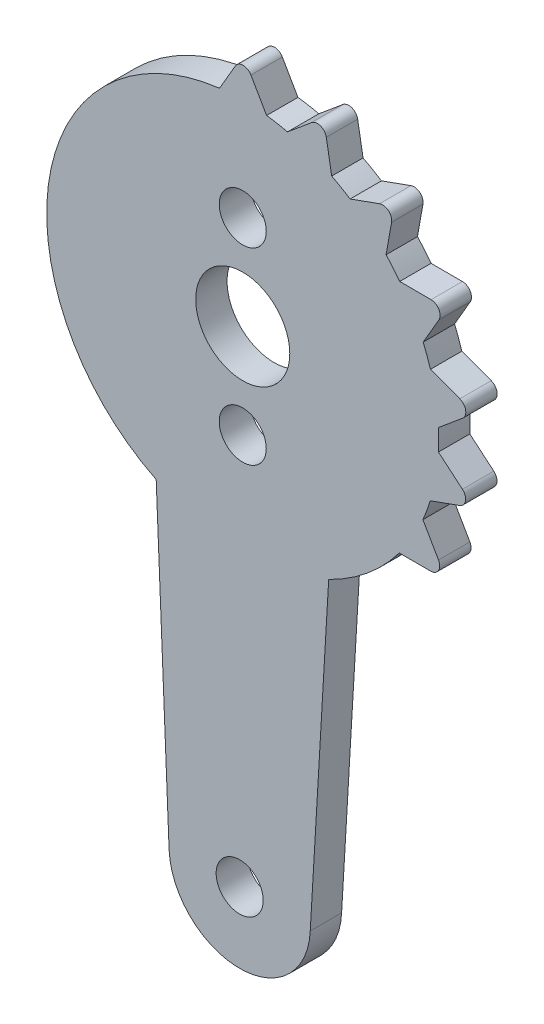
SolidWorks part; units mm, degrees
ref_plane "Front Plane" through (0, 0, 0) normal (0, 0, 1) x (1, 0, 0)
ref_plane "Top Plane" through (0, 0, 0) normal (0, 1, 0) x (1, 0, 0)
ref_plane "Right Plane" through (0, 0, 0) normal (1, 0, 0) x (0, 0, -1)
sketch "Sketch1" plane through (0, 0, 0) normal (0, 0, 1) x (1, 0, 0)
  line L0 (-5.3228, 19.8328) -> (-4.5, -0.185)
  line L1 (5.6772, 19.8147) -> (4.5, -0.1853)
  line L2 (4.5859, 44.5001) -> (3.0506, 43.2183)
  line L3 (0.7204, 45.1904) -> (1.7162, 43.4559)
  line L4 (-0.2796, 45.1904) -> (-1.2838, 43.4608)
  line L5 (5.5255, 44.158) -> (5.868, 42.1876)
  line L6 (8.9217, 42.1873) -> (7.0407, 41.5079)
  line L7 (9.6878, 41.5445) -> (9.3356, 39.5758)
  line L8 (12.2051, 38.5311) -> (10.2051, 38.536)
  line L9 (12.7051, 37.665) -> (11.7008, 35.9355)
  line L10 (14.04, 33.9723) -> (12.1623, 34.661)
  line L11 (14.2136, 32.9875) -> (12.6784, 31.7058)
  line L12 (14.205, 29.061) -> (12.6761, 30.3504)
  line L13 (14.0314, 28.0762) -> (12.1503, 27.3968)
  line L14 (12.6803, 24.3894) -> (11.6846, 26.1239)
  line L15 (12.1803, 23.5233) -> (10.1803, 23.5283)
  line L16 (0.1956, 31.0487) -> (0.1956, 37.0487) construction
  line L17 (0.1956, 31.0487) -> (0.1956, 25.0487) construction
  arc A0 (-5.3228, 19.8328) -> (-1.2838, 43.4608) centre (0.1956, 31.0487) cw
  arc A1 (-4.5, -0.185) -> (4.5, -0.1853) centre (0, 0) ccw
  circle A2 centre (0.1956, 31.0487) radius 3
  circle A3 centre (0.1956, 37.0487) radius 1.5
  circle A4 centre (0.1956, 25.0487) radius 1.5
  circle A5 centre (0, 0) radius 1.5
  arc A6 (-0.2796, 45.1904) -> (0.7204, 45.1904) centre (0.2204, 44.9001) cw
  arc A7 (1.7162, 43.4559) -> (3.0506, 43.2183) centre (0.1956, 31.0487) cw
  arc A8 (4.5859, 44.5001) -> (5.5255, 44.158) centre (4.9564, 44.0562) cw
  arc A9 (8.9217, 42.1873) -> (9.6878, 41.5445) centre (9.1181, 41.6435) cw
  arc A10 (12.2051, 38.5311) -> (12.7051, 37.665) centre (12.2037, 37.9529) cw
  arc A11 (14.04, 33.9723) -> (14.2136, 32.9875) centre (13.8409, 33.4295) cw
  arc A12 (14.205, 29.061) -> (14.0314, 28.0762) centre (13.8323, 28.619) cw
  arc A13 (12.6803, 24.3894) -> (12.1803, 23.5233) centre (12.1789, 24.1015) cw
  arc A14 (9.3356, 39.5758) -> (10.2051, 38.536) centre (0.1956, 31.0487) cw
  arc A15 (5.868, 42.1876) -> (7.0407, 41.5079) centre (0.1956, 31.0487) cw
  arc A16 (11.7008, 35.9355) -> (12.1623, 34.661) centre (0.1956, 31.0487) cw
  arc A17 (12.6784, 31.7058) -> (12.6761, 30.3504) centre (0.1956, 31.0487) cw
  arc A18 (12.1503, 27.3968) -> (11.6846, 26.1239) centre (0.1956, 31.0487) cw
  arc A19 (10.1803, 23.5283) -> (5.6772, 19.8147) centre (0.1956, 31.0487) cw
  point P50 (0.1956, 31.0487)
  dimension "D2" = 6
  dimension "D3" = 12.5
  dimension "D6" = 9
  dimension "D8" = 4.5038
  dimension "D11" = 3
  dimension "D5" = 6
  dimension "D4" = 6
  dimension "D17" = 3
  dimension "D18" = 3
  dimension "D7" = 11
  dimension "D9" = 20
  dimension "D10" = 31.0487
  dimension "D12" = 44.9001
  dimension "D13" = 7
  dimension "D14" = 2
  dimension "D15" = 2
  dimension "D16" = 1
extrude "Boss-Extrude1" add sketch "Sketch1" along normal blind 2
